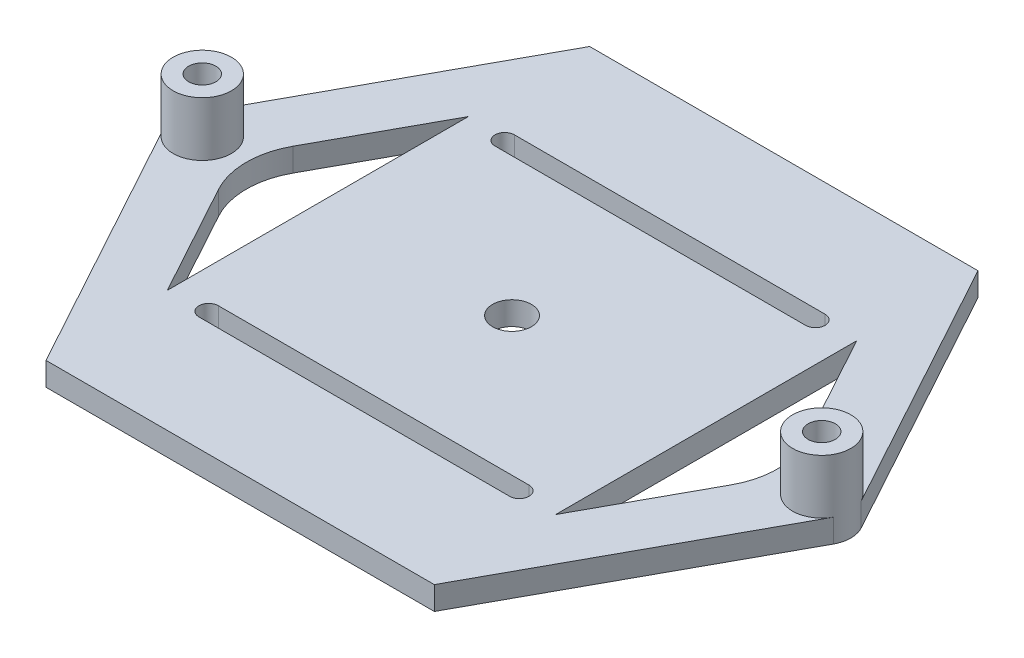
SolidWorks part; units mm, degrees
ref_plane "Front Plane" through (0, 0, 0) normal (0, 0, 1) x (1, 0, 0)
ref_plane "Top Plane" through (0, 0, 0) normal (0, 1, 0) x (1, 0, 0)
ref_plane "Right Plane" through (0, 0, 0) normal (1, 0, 0) x (0, 0, -1)
sketch "Sketch1" plane through (0, -100.2, 0) normal (0, -1, 0) x (1, 0, 0)
  line L0 (0, 50.3434) -> (0, -50) construction
  line L1 (-50, 0) -> (50, 0) construction
  line L2 (-50, 45) -> (-50, -45) construction
  line L3 (50, 45) -> (50, -45) construction
  line L4 (-39.8763, 39) -> (-39.8763, -39) construction
  arc A0 (-37.3604, 37.3604) -> (-42.6263, 36.25) centre (-39.8763, 36.25) ccw construction
  arc A1 (-42.6263, -36.25) -> (-37.3604, -37.3604) centre (-39.8763, -36.25) ccw construction
  circle A2 centre (-39.8763, 0) radius 1.75
  circle A3 centre (-39.8763, 0) radius 3.75
  circle A4 centre (39.8763, 0) radius 3.75
  circle A5 centre (39.8763, 0) radius 1.75
  dimension "D1" = 3.5
  dimension "D2" = 7.5
extrude "Boss-Extrude1" add sketch "Sketch1" along normal blind 10
sketch "Sketch2" plane through (0, -110.2, 0) normal (0, -1, 0) x (1, 0, 0)
  line L0 (-25, 35) -> (-43.166, 1.8)
  line L1 (25, -35) -> (-25, -35)
  line L2 (25, -19.3754) -> (25, 19.3754)
  line L3 (25, 35) -> (-25, 35)
  line L4 (-25, -19.3754) -> (-25, 19.3754)
  line L5 (25, -35) -> (-25, 35) construction
  line L6 (25, 35) -> (-25, -35) construction
  line L7 (-25, -35) -> (-43.166, -1.8)
  line L8 (-32.9751, 4.8001) -> (-25, 19.3754)
  line L9 (-32.9751, -4.8001) -> (-25, -19.3754)
  line L10 (0, 35) -> (0, -35) construction
  line L11 (32.9751, 4.8001) -> (25, 19.3754)
  line L12 (32.9751, -4.8001) -> (25, -19.3754)
  line L13 (25, -35) -> (43.166, -1.8)
  line L14 (25, 35) -> (43.166, 1.8)
  circle A0 centre (-39.8763, 0) radius 3.75 construction
  circle A1 centre (-39.8763, 0) radius 3.75
  circle A2 centre (-39.8763, 0) radius 1.75 construction
  circle A3 centre (-39.8763, 0) radius 1.75
  circle A4 centre (39.8763, 0) radius 3.75 construction
  circle A5 centre (39.8763, 0) radius 3.75
  circle A6 centre (39.8763, 0) radius 1.75 construction
  circle A7 centre (39.8763, 0) radius 1.75
  arc A8 (-32.9751, 4.8001) -> (-32.9751, -4.8001) centre (-24.2025, 0) ccw
  arc A9 (32.9751, 4.8001) -> (32.9751, -4.8001) centre (24.2025, 0) cw
  point P0 (0, 0)
  circle M8 centre (-39.8763, 0) radius 3.75
  dimension "D3" = 10
  dimension "D1" = 70
  dimension "D2" = 50
extrude "Boss-Extrude2" add sketch "Sketch2" against normal blind 3 contours A5 L14 L3 L0 L7 L1 L13 A8 L8 L4 L9 L11 A9 L12 L2 M8
sketch "Sketch3" plane through (0, -107.2, 0) normal (0, 1, 0) x (1, 0, 0)
  circle A0 centre (0, 0) radius 2.5
  point P0 (0, 0)
  dimension "D1" = 5
extrude "Cut-Extrude1" cut sketch "Sketch3" against normal through all
sketch "Sketch4" plane through (0, -107.2, 0) normal (0, 1, 0) x (1, 0, 0)
  line L0 (0, 0) -> (0, -35) construction
  line L1 (25, -35) -> (-25, -35) construction
  line L2 (0, 0) -> (25, 0) construction
  line L3 (20, -17.8079) -> (-20, -17.8079)
  line L4 (20, -20.3079) -> (-20, -20.3079)
  line L5 (25, 19.3754) -> (25, -19.3754) construction
  line L6 (20, 20.3079) -> (-20, 20.3079)
  line L7 (20, 17.8079) -> (-20, 17.8079)
  arc A1 (20, -20.3079) -> (20, -17.8079) centre (20, -19.0579) ccw
  arc A2 (-20, -20.3079) -> (-20, -17.8079) centre (-20, -19.0579) cw
  arc A3 (20, 20.3079) -> (20, 17.8079) centre (20, 19.0579) cw
  arc A4 (-20, 20.3079) -> (-20, 17.8079) centre (-20, 19.0579) ccw
  dimension "D2" = 2.5
  dimension "D3" = 20
extrude "Cut-Extrude2" cut sketch "Sketch4" against normal through all
